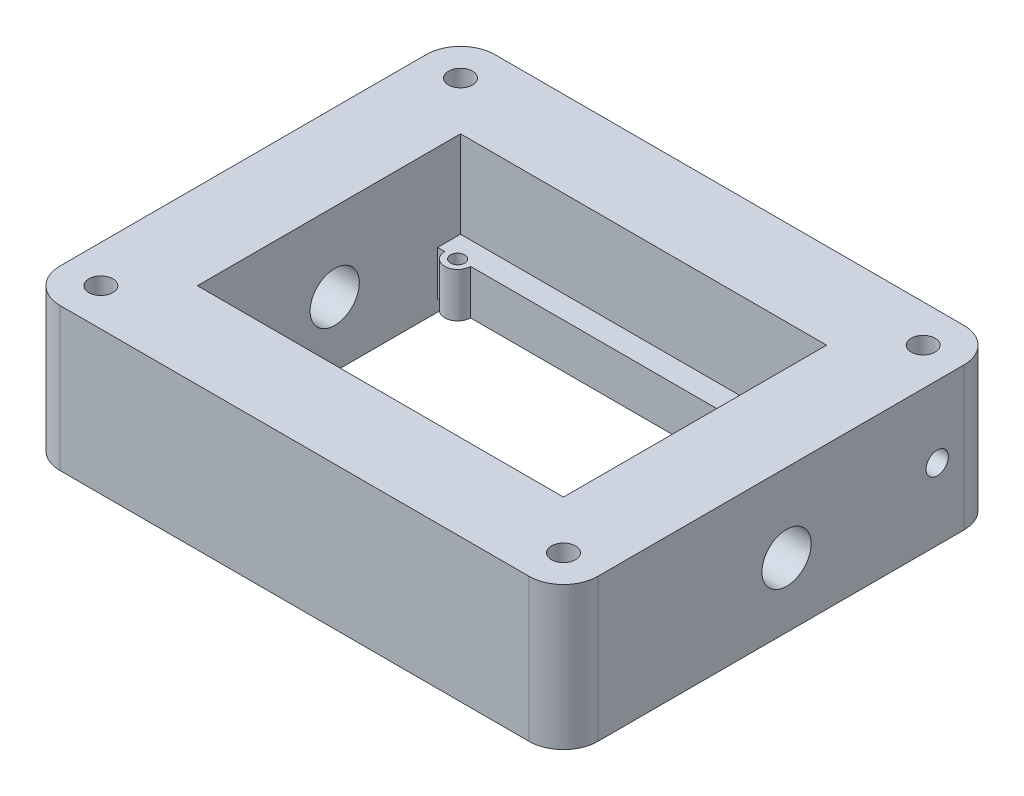
SolidWorks part; units mm, degrees
ref_plane "Front Plane" through (0, 0, 0) normal (0, 0, 1) x (1, 0, 0)
ref_plane "Top Plane" through (0, 0, 0) normal (0, 1, 0) x (1, 0, 0)
ref_plane "Right Plane" through (0, 0, 0) normal (1, 0, 0) x (0, 0, -1)
sketch "Sketch1" plane through (0, 0, 0) normal (0, 1, 0) x (1, 0, 0)
  line L0 (-32, 19) -> (-30.75, 19)
  line L1 (-47, -38) -> (47, -38)
  line L2 (-47, -38) -> (-47, 38)
  line L3 (-47, 38) -> (47, 38)
  line L4 (47, -38) -> (47, 38)
  line L5 (-47, -38) -> (47, 38) construction
  line L6 (-47, 38) -> (47, -38) construction
  line L7 (32, 23) -> (-32, 23)
  line L8 (32, 23) -> (32, -23)
  line L9 (32, -23) -> (-32, -23)
  line L10 (-32, 23) -> (-32, -23)
  line L11 (32, 23) -> (-32, -23) construction
  line L12 (32, -23) -> (-32, 23) construction
  line L13 (-32, -19) -> (-30.75, -19)
  line L14 (-26.25, 19) -> (26.4348, 19)
  line L16 (30.75, 19) -> (32, 19)
  line L19 (30.75, -19) -> (32, -19)
  line L21 (-26.25, -19) -> (26.25, -19)
  arc A0 (-30.75, 19) -> (-26.25, 19) centre (-28.5, 19) ccw
  arc A2 (26.25, 19) -> (30.75, 19) centre (28.5, 19) ccw
  arc A4 (30.75, -19) -> (26.25, -19) centre (28.5, -19) ccw
  arc A6 (-26.25, -19) -> (-30.75, -19) centre (-28.5, -19) ccw
  circle A8 centre (-28.5, 19) radius 1.25
  circle A9 centre (28.5, -19) radius 1.25
  circle A10 centre (-28.5, -19) radius 1.25
  circle A11 centre (28.5, 19) radius 1.25
  point P0 (0, 0)
  point P6 (0, 0)
  dimension "D8" = 4.5
  dimension "D9" = 2.5
  dimension "D10" = 4.5
  dimension "D11" = 2.5
  dimension "D14" = 2.5
  dimension "D15" = 4.5
  dimension "D16" = 4.5
  dimension "D17" = 2.5
  dimension "D1" = 94
  dimension "D2" = 76
  dimension "D3" = 46
  dimension "D4" = 64
  dimension "D5" = 4
  dimension "D6" = 4
  dimension "D7" = 3.5
  dimension "D12" = 3.5
  dimension "D13" = 3.5
  dimension "D18" = 3.5
extrude "Boss-Extrude1" add sketch "Sketch1" along normal blind 9.8
sketch "Sketch2" plane through (0, 9.8, 0) normal (0, 1, 0) x (1, 0, 0)
  line L1 (-47, -38) -> (47, -38)
  line L2 (-47, -38) -> (-47, 38)
  line L3 (-47, 38) -> (47, 38)
  line L4 (47, -38) -> (47, 38)
  line L5 (-47, -38) -> (47, 38) construction
  line L6 (-47, 38) -> (47, -38) construction
  line L7 (-32, -23) -> (32, -23)
  line L8 (-32, -23) -> (-32, 23)
  line L9 (-32, 23) -> (32, 23)
  line L10 (32, -23) -> (32, 23)
  line L11 (-32, -23) -> (32, 23) construction
  line L12 (-32, 23) -> (32, -23) construction
  point P0 (0, 0)
  point P7 (0, 0)
  dimension "D1" = 46
  dimension "D2" = 64
extrude "Boss-Extrude3" add sketch "Sketch2" along normal blind 15.2
sketch "Sketch3" plane through (0, 0, 0) normal (0, -1, 0) x (1, 0, 0)
  line L1 (-32, -23) -> (32, -23)
  line L2 (-32, -23) -> (-32, 23)
  line L3 (-32, 23) -> (32, 23)
  line L4 (32, -23) -> (32, 23)
  line L5 (-32, -23) -> (32, 23) construction
  line L6 (-32, 23) -> (32, -23) construction
  point P0 (0, 0)
  dimension "D1" = 64
  dimension "D2" = 46
extrude "Cut-Extrude1" cut sketch "Sketch3" against normal blind 2
sketch "Sketch4" plane through (47, 0, 0) normal (1, 0, 0) x (0, 0, -1)
  line L0 (0, 0) -> (0, 25) construction
  line L1 (-38, 25) -> (38, 25) construction
  line L3 (19, 9.8) -> (23, 9.8) construction
  circle A0 centre (1, 11.3) radius 4.305
  dimension "D3" = 8.61
  dimension "D1" = 1.5
  dimension "D2" = 1
extrude "Cut-Extrude2" cut sketch "Sketch4" against normal through all both and the other way through all
sketch "Sketch5" plane through (0, 25, 0) normal (0, 1, 0) x (1, 0, 0)
  line L0 (47, 38) -> (-47, 38) construction
  line L1 (-47, 38) -> (-47, -38) construction
  circle A0 centre (-40.44, 31.44) radius 2.1
  circle A1 centre (40.44, 31.44) radius 2.1
  circle A2 centre (40.44, -31.44) radius 2.1
  circle A3 centre (-40.44, -31.44) radius 2.1
  dimension "D1" = 4.2
  dimension "D2" = 6.56
  dimension "D3" = 6.56
  dimension "D4" = 2
  dimension "D5" = 2
extrude "Cut-Extrude3" cut sketch "Sketch5" against normal through all both and the other way through all
fillet "Fillet1" radius 6 4 edges at (-47, 12.5, -38) (47, 12.5, -38) (47, 12.5, 38) (-47, 12.5, 38)
ref_plane "Plane3" through (0, 12.5, 0) normal (0, -1, 0) x (-1, 0, 0)
sketch "Sketch9" plane through (0, 12.5, 0) normal (0, -1, 0) x (-1, 0, 0)
  line L10 (-47, 27.34) -> (-40.44, 27.34)
  line L11 (-47, -32) -> (-47, 32) construction
  line L12 (-36.34, 38) -> (-36.34, 31.44)
  line L13 (41, 38) -> (-41, 38) construction
  circle A3 centre (-40.44, 31.44) radius 2.1 construction
  arc A4 (-40.44, 27.34) -> (-36.34, 31.44) centre (-40.44, 31.44) ccw
  dimension "D3" = 4.1
  dimension "D1" = 4.1
  dimension "D2" = 4.1
sweep "Cut-Sweep" cut path "Sketch9" circular profile diameter 3.9 parameters "D3"=3.9
